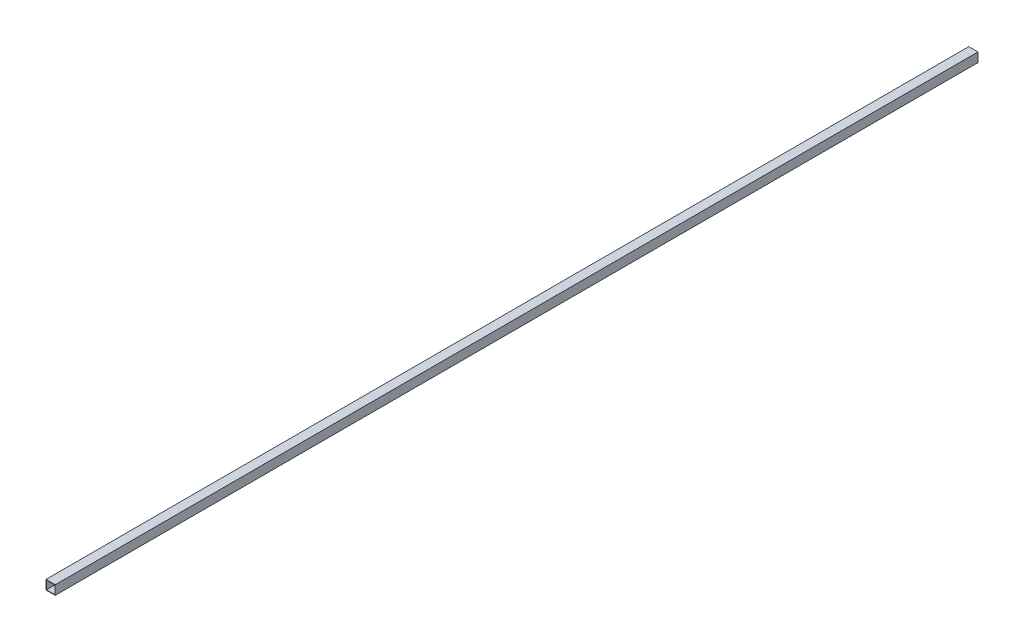
SolidWorks part; units mm, degrees
ref_plane "Plan de face" through (0, 0, 0) normal (0, 0, 1) x (1, 0, 0)
ref_plane "Plan de dessus" through (0, 0, 0) normal (0, 1, 0) x (1, 0, 0)
ref_plane "Plan de droite" through (0, 0, 0) normal (1, 0, 0) x (0, 0, -1)
sketch "Esquisse1" plane through (0, 0, 0) normal (0, 0, 1) x (1, 0, 0)
  line L0 (-450, 450) -> (450, 450)
  line L1 (-500, -500) -> (500, -500)
  line L2 (-500, -500) -> (-500, 500)
  line L3 (-500, 500) -> (500, 500)
  line L4 (500, -500) -> (500, 500)
  line L5 (-500, -500) -> (500, 500) construction
  line L6 (-500, 500) -> (500, -500) construction
  line L7 (450, -450) -> (450, 450)
  line L8 (-450, -450) -> (450, -450)
  line L9 (-450, -450) -> (-450, 450)
  point P0 (0, 0)
  dimension "D1" = 1000
  dimension "D2" = 1000
  dimension "D3" = 50
extrude "Boss.-Extru.1" add sketch "Esquisse1" along normal blind 100000
